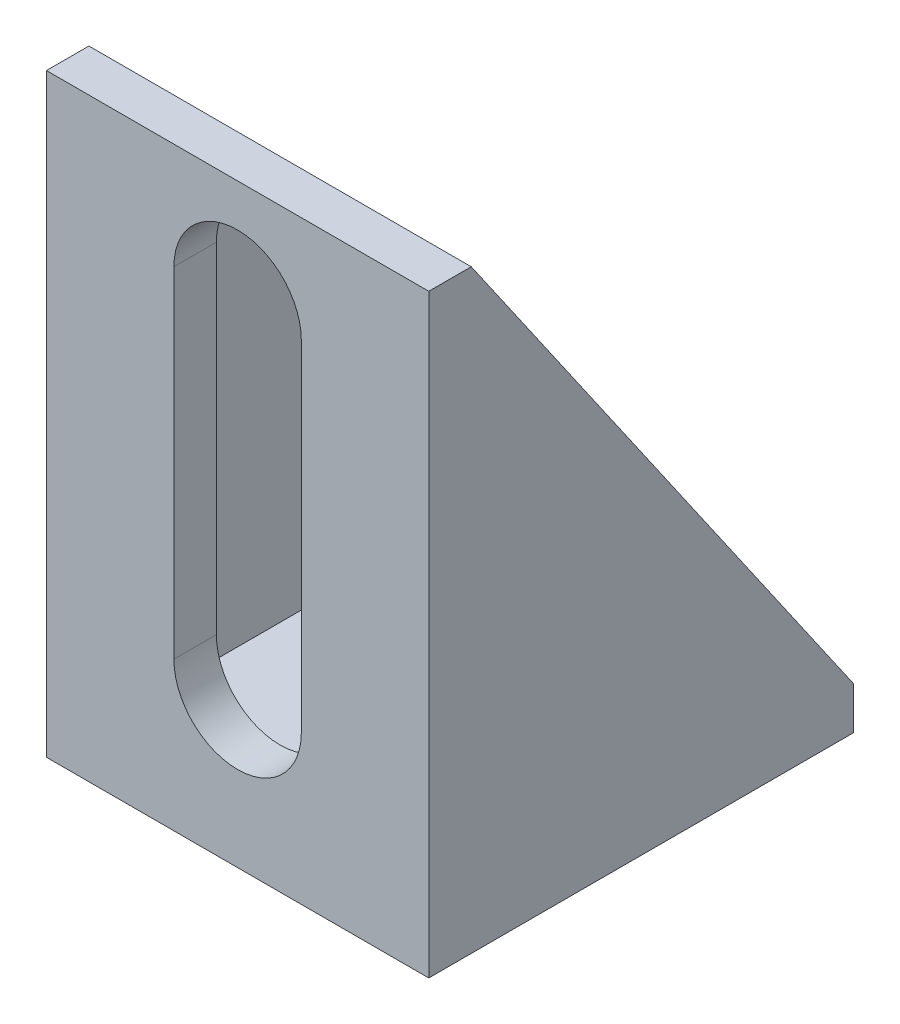
SolidWorks part; units mm, degrees
ref_plane "정면" through (0, 0, 0) normal (0, 0, 1) x (1, 0, 0)
ref_plane "윗면" through (0, 0, 0) normal (0, 1, 0) x (1, 0, 0)
ref_plane "우측면" through (0, 0, 0) normal (1, 0, 0) x (0, 0, -1)
sketch "스케치1" plane through (0, 0, 0) normal (1, 0, 0) x (0, 0, -1)
  line L0 (0, 0) -> (20, 0)
  line L1 (20, 0) -> (20, 2)
  line L2 (20, 2) -> (2, 28)
  line L3 (2, 28) -> (0, 28)
  line L4 (0, 28) -> (0, 0)
  dimension "D1" = 20
  dimension "D2" = 28
  dimension "D3" = 2
  dimension "D4" = 2
extrude "보스-돌출1" add sketch "스케치1" along normal blind 18
sketch "스케치2" plane through (0, 0, -20) normal (0, 0, -1) x (-1, 0, 0)
  line L0 (-18, 2) -> (0, 2) construction
  line L1 (-16, 2) -> (-2, 2)
  line L2 (-16, 2) -> (-16, 28)
  line L3 (-16, 28) -> (-2, 28)
  line L4 (-2, 2) -> (-2, 28)
  line L5 (-18, 28) -> (0, 28) construction
  line L6 (0, 2) -> (0, 28) construction
  line L7 (-18, 2) -> (-18, 28) construction
  dimension "D1" = 2
  dimension "D2" = 2
extrude "컷-돌출1" cut sketch "스케치2" against normal blind 18
sketch "스케치3" plane through (0, 0, -2) normal (0, 0, -1) x (-1, 0, 0)
  line L0 (-9, 23) -> (-9, 7) construction
  line L1 (-6, 23) -> (-6, 7)
  line L2 (-12, 23) -> (-12, 7)
  line L3 (-9, 28) -> (-9, 23) construction
  line L4 (-2, 28) -> (-16, 28) construction
  line L5 (-9, 7) -> (-9, 2) construction
  line L6 (-16, 2) -> (-2, 2) construction
  arc A0 (-6, 23) -> (-12, 23) centre (-9, 23) ccw
  arc A1 (-12, 7) -> (-6, 7) centre (-9, 7) ccw
  point P2 (-9, 15)
  dimension "D1" = 3
  dimension "D2" = 16
extrude "컷-돌출2" cut sketch "스케치3" against normal blind 18
sketch "스케치4" plane through (0, 2, 0) normal (0, 1, 0) x (1, 0, 0)
  line L0 (9, 20) -> (9, 2) construction
  line L1 (16, 20) -> (2, 20) construction
  line L2 (2, 2) -> (16, 2) construction
  circle A0 centre (9, 11) radius 3
  dimension "D1" = 6
extrude "컷-돌출3" cut sketch "스케치4" against normal blind 18
